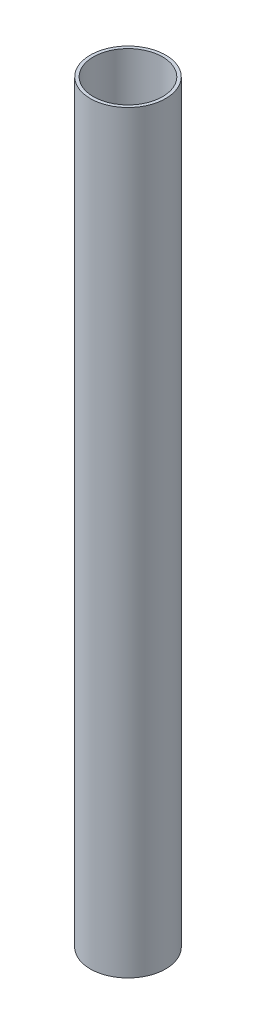
SolidWorks part; units mm, degrees
ref_plane "Plano frontal" through (0, 0, 0) normal (0, 0, 1) x (1, 0, 0)
ref_plane "Plano superior" through (0, 0, 0) normal (0, 1, 0) x (1, 0, 0)
ref_plane "Plano direito" through (0, 0, 0) normal (1, 0, 0) x (0, 0, -1)
sketch3d "3DSketch1"
  line L0 (0, 0, 0) -> (0, 600, 0)
  dimension "D1" = 600
sweep "Varredura1" add path "3DSketch1" circular profile diameter 60 parameters "D3"=60
shell "Casca1" thickness 2.5
